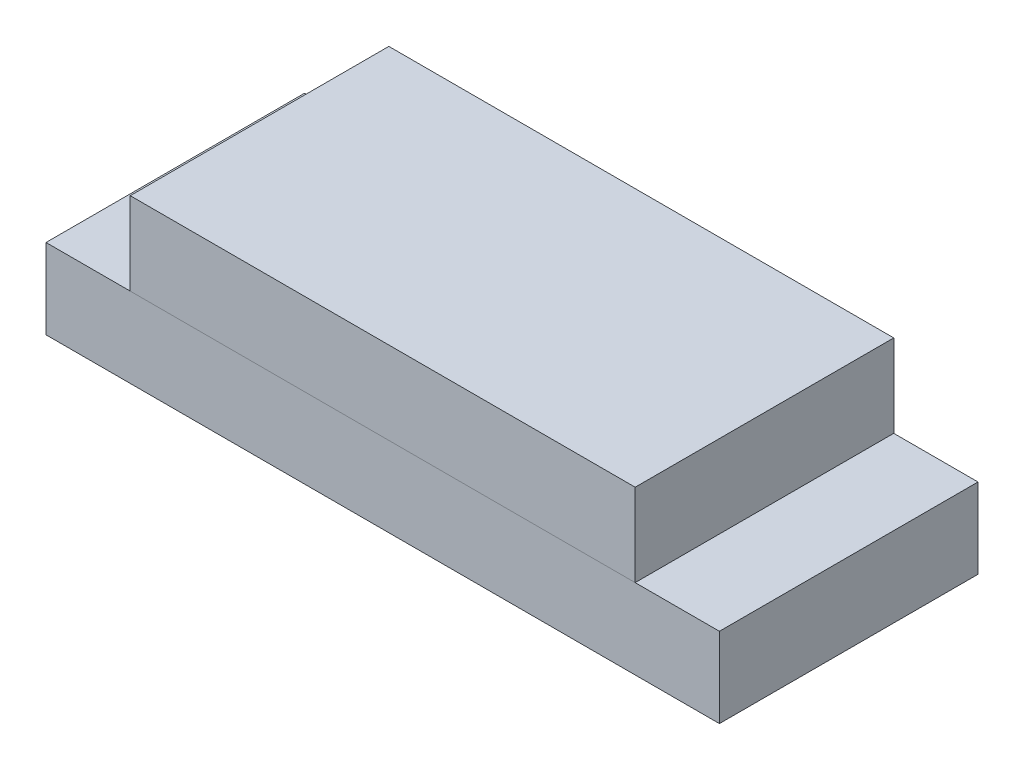
SolidWorks part; units mm, degrees
ref_plane "Front Plane" through (0, 0, 0) normal (0, 0, 1) x (1, 0, 0)
ref_plane "Top Plane" through (0, 0, 0) normal (0, 1, 0) x (1, 0, 0)
ref_plane "Right Plane" through (0, 0, 0) normal (1, 0, 0) x (0, 0, -1)
sketch "Sketch1" plane through (0, 0, 0) normal (0, 0, 1) x (1, 0, 0)
  line L1 (64.1604, 7.62) -> (0, 7.62)
  line L2 (64.1604, 7.62) -> (64.1604, 0)
  line L3 (64.1604, 0) -> (0, 0)
  line L4 (0, 7.62) -> (0, 0)
  dimension "D1" = 64.1604
  dimension "D2" = 7.62
extrude "Boss-Extrude1" add sketch "Sketch1" along normal blind 24.638 contours L1 L4 L3 L2
sketch "Sketch2" plane through (0, 0, 0) normal (0, 0, -1) x (-1, 0, 0)
  line L0 (-64.1604, 7.62) -> (0, 7.62) construction
  line L1 (-56.134, 7.62) -> (-8.0264, 7.62)
  line L2 (-56.134, 7.62) -> (-56.134, 15.494)
  line L3 (-56.134, 15.494) -> (-8.0264, 15.494)
  line L4 (-8.0264, 7.62) -> (-8.0264, 15.494)
  line L5 (-64.1604, 7.62) -> (0, 7.62) construction
  point P6 (-32.0802, 7.62)
  point P9 (-32.0802, 7.62)
  dimension "D1" = 48.1076
  dimension "D2" = 7.874
extrude "Boss-Extrude2" add sketch "Sketch2" against normal blind 24.638 separate body
